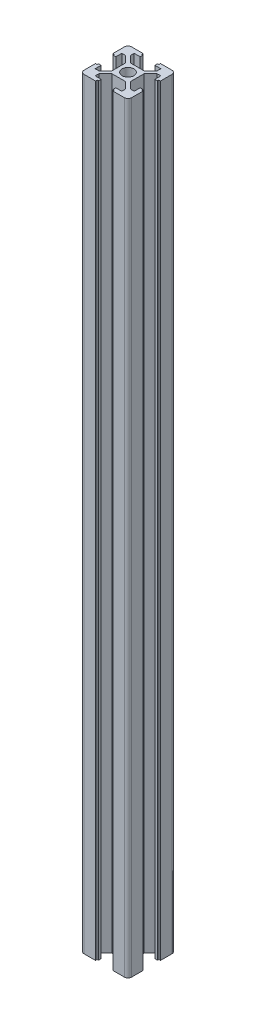
SolidWorks part; units mm, degrees
ref_plane "前视基准面" through (0, 0, 0) normal (0, 0, 1) x (1, 0, 0)
ref_plane "上视基准面" through (0, 0, 0) normal (0, 1, 0) x (1, 0, 0)
ref_plane "右视基准面" through (0, 0, 0) normal (1, 0, 0) x (0, 0, -1)
sketch "草图1" plane through (0, 0, 0) normal (0, 1, 0) x (1, 0, 0)
  line L0 (-10, 0) -> (10, 0) construction
  line L2 (10, 10) -> (3.65, 10)
  line L4 (-3.65, 10) -> (-3.65, 9.3033)
  line L5 (-3.65, 9.3033) -> (-3.1, 9.3033)
  line L6 (-3.1, 9.3033) -> (-3.1, 8.2)
  line L7 (-3.1, 8.2) -> (-5.6, 8.2)
  line L8 (-5.6, 8.2) -> (-5.6, 6.6607)
  line L9 (-5.6, 6.6607) -> (-2.8393, 3.9)
  line L11 (5.6, 6.6607) -> (5.6, 8.2)
  line L12 (5.6, 8.2) -> (3.1, 8.2)
  line L13 (3.1, 8.2) -> (3.1, 9.3033)
  line L14 (3.1, 9.3033) -> (3.65, 9.3033)
  line L15 (3.65, 9.3033) -> (3.65, 10)
  line L16 (-3.65, 10) -> (-10, 10)
  line L17 (0, 0) -> (0, 16.5896) construction
  line L18 (-2.8393, 3.9) -> (2.8393, 3.9)
  line L19 (2.8393, 3.9) -> (5.6, 6.6607)
  line L20 (10, -10) -> (10, -3.65)
  line L21 (10, 3.65) -> (9.3033, 3.65)
  line L22 (9.3033, 3.65) -> (9.3033, 3.1)
  line L23 (9.3033, 3.1) -> (8.2, 3.1)
  line L24 (8.2, 3.1) -> (8.2, 5.6)
  line L25 (8.2, 5.6) -> (6.6607, 5.6)
  line L26 (6.6607, 5.6) -> (3.9, 2.8393)
  line L27 (6.6607, -5.6) -> (8.2, -5.6)
  line L28 (8.2, -5.6) -> (8.2, -3.1)
  line L29 (8.2, -3.1) -> (9.3033, -3.1)
  line L30 (9.3033, -3.1) -> (9.3033, -3.65)
  line L31 (9.3033, -3.65) -> (10, -3.65)
  line L32 (10, 3.65) -> (10, 10)
  line L33 (3.9, 2.8393) -> (3.9, -2.8393)
  line L34 (3.9, -2.8393) -> (6.6607, -5.6)
  line L35 (0, 10) -> (0, -10) construction
  line L36 (0, 0) -> (16.5896, 0) construction
  line L37 (-10, -10) -> (-3.65, -10)
  line L38 (3.65, -10) -> (3.65, -9.3033)
  line L39 (3.65, -9.3033) -> (3.1, -9.3033)
  line L40 (3.1, -9.3033) -> (3.1, -8.2)
  line L41 (3.1, -8.2) -> (5.6, -8.2)
  line L42 (5.6, -8.2) -> (5.6, -6.6607)
  line L43 (5.6, -6.6607) -> (2.8393, -3.9)
  line L44 (-5.6, -6.6607) -> (-5.6, -8.2)
  line L45 (-5.6, -8.2) -> (-3.1, -8.2)
  line L46 (-3.1, -8.2) -> (-3.1, -9.3033)
  line L47 (-3.1, -9.3033) -> (-3.65, -9.3033)
  line L48 (-3.65, -9.3033) -> (-3.65, -10)
  line L49 (3.65, -10) -> (10, -10)
  line L50 (2.8393, -3.9) -> (-2.8393, -3.9)
  line L51 (-2.8393, -3.9) -> (-5.6, -6.6607)
  line L52 (10, 0) -> (-10, 0) construction
  line L53 (0, 0) -> (0, -16.5896) construction
  line L54 (-10, 10) -> (-10, 3.65)
  line L55 (-10, -3.65) -> (-9.3033, -3.65)
  line L56 (-9.3033, -3.65) -> (-9.3033, -3.1)
  line L57 (-9.3033, -3.1) -> (-8.2, -3.1)
  line L58 (-8.2, -3.1) -> (-8.2, -5.6)
  line L59 (-8.2, -5.6) -> (-6.6607, -5.6)
  line L60 (-6.6607, -5.6) -> (-3.9, -2.8393)
  line L61 (-6.6607, 5.6) -> (-8.2, 5.6)
  line L62 (-8.2, 5.6) -> (-8.2, 3.1)
  line L63 (-8.2, 3.1) -> (-9.3033, 3.1)
  line L64 (-9.3033, 3.1) -> (-9.3033, 3.65)
  line L65 (-9.3033, 3.65) -> (-10, 3.65)
  line L66 (-10, -3.65) -> (-10, -10)
  line L67 (-3.9, -2.8393) -> (-3.9, 2.8393)
  line L68 (-3.9, 2.8393) -> (-6.6607, 5.6)
  line L69 (0, -10) -> (0, 10) construction
  line L70 (0, 0) -> (-16.5896, 0) construction
  circle A0 centre (0, 0) radius 2.5
  point P12 (0, 3.9)
  dimension "D8" = 1.5
  dimension "D10" = 5
  dimension "D1" = 20
  dimension "D2" = 10
  dimension "D3" = 7.3
  dimension "D4" = 6.2
  dimension "D5" = 1.8
  dimension "D6" = 4.3
  dimension "D7" = 11.2
  dimension "D9" = 4
extrude "凸台-拉伸1" add sketch "草图1" along normal blind 320
fillet "圆角1" radius 1.5 4 edges at (-10, 160, 10) (-10, 160, -10) (10, 160, 10) (10, 160, -10)
